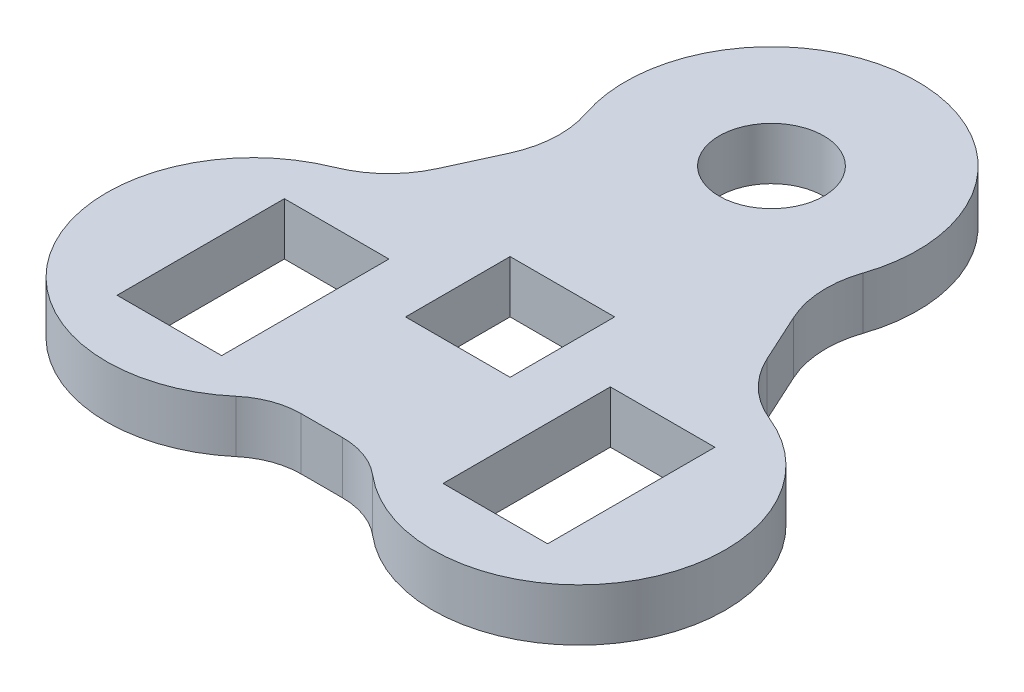
SolidWorks part; units mm, degrees
ref_plane "Front Plane" through (0, 0, 0) normal (0, 0, 1) x (1, 0, 0)
ref_plane "Top Plane" through (0, 0, 0) normal (0, 1, 0) x (1, 0, 0)
ref_plane "Right Plane" through (0, 0, 0) normal (1, 0, 0) x (0, 0, -1)
sketch "Sketch1" plane through (0, 0, 0) normal (0, 1, 0) x (1, 0, 0)
  line L0 (0, 0) -> (0, 300) construction
  line L1 (0, 0) -> (0, -77.4253) construction
  line L2 (0, 0) -> (259.8076, -150) construction
  line L3 (0, 0) -> (-259.8076, -150) construction
  line L4 (0, 60.4932) -> (0, -180) construction
  line L5 (-50, 50) -> (50, 50)
  line L6 (-50, 50) -> (-50, -50)
  line L7 (-50, -50) -> (50, -50)
  line L8 (50, 50) -> (50, -50)
  line L9 (205.8846, -170) -> (105.8846, -170)
  line L10 (-205.8846, -10) -> (-105.8846, -10)
  line L11 (-19.7979, -180) -> (18.2754, -180) construction
  line L12 (-157.6313, 88.0712) -> (-136.6634, 133.755)
  line L13 (-292.3953, -205.546) -> (-11.1841, 407.1433) construction
  line L14 (-117.123, 98.0626) -> (-176.4233, 125.2802) construction
  line L15 (157.6313, 88.0712) -> (136.6634, 133.755)
  line L16 (19.7979, -180) -> (-19.7979, -180)
  line L17 (-205.8846, -10) -> (-205.8846, -170)
  line L18 (-205.8846, -170) -> (-105.8846, -170)
  line L19 (135.9582, 135.2915) -> (136.6634, 133.755)
  line L20 (-135.9582, 135.2915) -> (-136.6634, 133.755)
  line L21 (-105.8846, -10) -> (-105.8846, -170)
  line L22 (-205.8846, -10) -> (-105.8846, -170) construction
  line L23 (-205.8846, -170) -> (-105.8846, -10) construction
  line L24 (105.8846, -10) -> (105.8846, -170)
  line L25 (205.8846, -10) -> (105.8846, -10)
  line L26 (205.8846, -10) -> (205.8846, -170)
  line L27 (-155.8846, -90) -> (-275.7067, -162.3983)
  circle A0 centre (0, 250) radius 50
  arc A1 (132.3634, 205.0564) -> (-132.3634, 205.0564) centre (0, 250) ccw
  arc A2 (-208.1852, 39.8596) -> (-65.2529, -196.6994) centre (-155.8846, -90) ccw
  arc A4 (-19.7979, -180) -> (-65.2529, -196.6994) centre (-19.7979, -250.2128) ccw
  arc A5 (19.7979, -180) -> (65.2529, -196.6994) centre (19.7979, -250.2128) cw
  arc A6 (-157.6313, 88.0712) -> (-208.1852, 39.8596) centre (-243.4699, 127.4693) cw
  arc A7 (-135.9582, 135.2915) -> (-132.3634, 205.0564) centre (-221.7968, 174.6895) ccw
  arc A8 (157.6313, 88.0712) -> (208.1852, 39.8596) centre (243.4699, 127.4693) ccw
  arc A9 (135.9582, 135.2915) -> (132.3634, 205.0564) centre (221.7968, 174.6895) cw
  arc A11 (65.2529, -196.6994) -> (208.1852, 39.8596) centre (155.8846, -90) ccw
  point P23 (0, -180)
  dimension "D3" = 250
  dimension "D5" = 180
  dimension "D1" = 60
  dimension "D2" = 60
  dimension "D4" = 300
  dimension "D6" = 180
  dimension "D7" = 180
  dimension "D8" = 180
  dimension "D9" = 100
  dimension "D10" = 100
extrude "Boss-Extrude1" add sketch "Sketch1" along normal blind 50 contours L20 L12 A6 A2 A4 L16 A5 A11 A8 L15 L19 A9 A1 A7 | L17 L10 L21 L18 | L9 L24 L25 L26 | A0 | L6 L5 L8 L7
sketch3d "3DSketch1"
  line L0 (-206.8457, 250, -38.8398) -> (-65.6839, 250, 196.9361)
  line L1 (-136.2648, 250, 79.0482) -> (-275.6963, 250, 162.5275)
  line L2 (0.3604, 250, 181.6694) -> (0.3604, 250, 1.3094)
  line L3 (207.5666, 250, -38.8398) -> (66.4047, 250, 196.9361)
  line L4 (136.9856, 250, 79.0482) -> (276.4171, 250, 162.5275)
  line L5 (0.3604, 250, -388.8632) -> (0.3604, 250, -249.704)
  line L6 (0.3604, 250, -249.704) -> (132.6177, 250, -203.791)
  line L7 (0.3604, 250, -249.704) -> (-129.9329, 250, -203.791)
  line L8 (-275.6963, 250, 162.5275) -> (-220.5482, 250, 254.6387)
  dimension "D1" = 200
ref_plane "Plane3" through (-274.5297, -0.0735, 164.3642) normal (0.858, 0.0002, -0.5137) x (-0.5137, -0.0001, -0.858)
sketch "Sketch3" plane through (-274.5297, -0.0735, 164.3642) normal (0.858, 0.0002, -0.5137) x (-0.5137, -0.0001, -0.858)
  line L0 (2.2913, 0.0738) -> (2.2913, 50.1852)
  line L1 (2.1408, 250.0738) -> (2.2913, 50.1852)
ref_plane "Plane5" through (-1.177, 0.0011, -1.9659) normal (0.5137, -0.0005, 0.858) x (0.858, 0.0003, -0.5137)
sketch "Sketch5" plane through (-1.177, 0.0011, -1.9659) normal (0.5137, -0.0005, 0.858) x (0.858, 0.0003, -0.5137)
  line L0 (-157.4486, 249.9789) -> (-157.0128, 50.1065)
sketch "Sketch4" plane through (-1.177, 0.0011, -1.9659) normal (0.5137, -0.0005, 0.858) x (0.858, 0.0003, -0.5137)
  line L0 (-319.9599, 250.088) -> (-319.9697, 50.1994) construction
  line L1 (-319.9697, 154.6685) -> (-319.9697, -54.2698) construction
  line L2 (-156.6033, 249.9789) -> (-230.1886, 249.9789) construction
  spline S0 degree 3 poles (-319.9697, 50.1994) (-319.9697, 167.7271) (-245.1663, 254.8296) (-152.1557, 249.7329) (-136.5823, 249.9789) knots 0 0 0 0 0.832545 1 1 1 1
sketch3d "3DSketch3"
  line L0 (-206.8457, 250, -38.8398) -> (-65.6839, 250, 196.9361) construction
  line L1 (-136.0562, 0, 78.5521) -> (-173.7166, 0, 228.8556)
  line L2 (0, 0, 0) -> (-259.8076, 0, 150) construction
  line L3 (-136.0562, 0, 78.5521) -> (-65.2529, 0, 196.6994)
  line L4 (-145.0356, 249.9014, 64.3987) -> (-142.8636, 250.0986, 68.0265) construction
  arc A0 (-208.1852, 0, -39.8596) -> (-65.2529, 0, 196.6994) centre (-155.8846, 0, 90) ccw construction
  arc A1 (-208.1852, 50, -39.8596) -> (-65.2529, 50, 196.6994) centre (-155.8846, 50, 90) ccw construction
  spline S0 degree 3 poles (-65.633, 50, 197.0211) (-66.083, 180.091, 196.2695) (-87.1022, 251.1553, 161.1621) (-142.5921, 250.1232, 68.4799) (-143.9496, 250, 66.2126) knots 0 0 0 0 0.94194 1 1 1 1
  spline S1 degree 3 poles (-206.9921, 50.1279, -39.0842) (-206.48, 180.2181, -38.2288) (-185.4268, 251.2442, -3.0648) (-129.9374, 250.1117, 89.6165) (-128.58, 249.9861, 91.8837) knots 0 0 0 0 0.94194 1 1 1 1
  point P12 (-155.8846, 139.9959, 90)
  point P21 (-155.8846, 189.9959, 90)
  dimension "D1" = 45
ref_plane "Plane6" through (-65.6839, 250, 196.9361) normal (0.5137, 0, 0.858) x (0.858, 0, -0.5137)
sketch "Sketch6" plane through (0, 250, 0) normal (0, 1, 0) x (1, 0, 0)
  line L0 (-222.8211, 0) -> (213.4028, 0) construction
  line L1 (0, 186.4295) -> (0, -206.6386) construction
  line L2 (0, 0) -> (0, 300) construction
  line L3 (-275.7067, -162.3983) -> (0, 0) construction
  line L4 (0, 0) -> (276.4171, -162.5275) construction
  line L5 (0.3604, 388.8632) -> (0, 0) construction
  line L6 (0, 0) -> (132.3634, 205.0564) construction
  line L7 (0, 0) -> (136.6634, 133.755) construction
  line L8 (0, 0) -> (157.6313, 88.0712) construction
  line L9 (-208.1852, 39.8596) -> (0, 0) construction
  line L10 (208.1852, 39.8596) -> (0, 0) construction
  line L11 (0, 0) -> (-157.6313, 88.0712) construction
  line L12 (0, 0) -> (-136.6634, 133.755) construction
  line L13 (0, 0) -> (-132.3634, 205.0564) construction
  line L14 (0, 0) -> (65.2529, -196.6994) construction
  line L15 (-19.7979, -180) -> (0, 0) construction
  line L16 (0, 0) -> (-65.2529, -196.6994) construction
  line L17 (19.7979, -180) -> (0, 0) construction
  line L18 (0, 0) -> (-122.4904, -72.15)
  ellipse E0 centre (0, 0) end of major axis (-150, 0) minor radius 125
ref_plane "Plane8" through (0, 500, 0) normal (0, 1, 0) x (1, 0, 0)
sketch "Sketch10" plane through (0, 500, 0) normal (0, 1, 0) x (1, 0, 0)
  line L0 (0, 0) -> (132.3634, 205.0564)
  line L1 (136.6634, 133.755) -> (0, 0)
  line L2 (157.6313, 88.0712) -> (0, 0)
  line L3 (0, 0) -> (208.1852, 39.8596)
  line L4 (0, 0) -> (65.2529, -196.6994)
  line L5 (19.7979, -180) -> (0, 0)
  line L6 (-275.7067, -162.3983) -> (0, 0)
  line L7 (0, 0) -> (0, -180)
  line L8 (0, 0) -> (0.3604, 388.8632)
  line L9 (275.4052, -162.9091) -> (0, 0)
  line L10 (-20.1316, -179.963) -> (0, 0)
  line L11 (0, 0) -> (-65.6174, -196.5781)
  line L12 (0, 0) -> (-208.111, 40.2454)
  line L13 (-157.4678, 88.3633) -> (0, 0)
  line L14 (-136.4152, 134.0081) -> (0, 0)
  line L15 (0, 0) -> (-131.9831, 205.3014)
  ellipse E0 centre (0, 0) end of major axis (150, 0) minor radius 125
ref_plane "Plane9" through (0, 0, 0) normal (-0.5075, 0, -0.8616) x (-0.8616, 0, 0.5075)
sketch "Sketch11" plane through (0, 0, 0) normal (-0.5075, 0, -0.8616) x (-0.8616, 0, 0.5075)
  line L0 (319.9803, 500) -> (0, 500)
  line L1 (319.9803, 0) -> (319.9803, 50) construction
  line L2 (0, 0) -> (0, 500) construction
  line L3 (0, 250) -> (319.9803, 250) construction
  line L4 (159.9902, 250) -> (159.9902, 500) construction
  line L5 (319.9803, 50) -> (0, 50) construction
  line L6 (159.9902, 250) -> (159.9902, 50) construction
  point P0 (0, 0)
  point P1 (319.9803, 0)
  point P3 (0, 500)
  point P9 (141.8948, 500)
sketch "Sketch12" plane through (0, 0, 0) normal (-0.5075, 0, -0.8616) x (-0.8616, 0, 0.5075)
  line L0 (190.1437, 235.0732) -> (190.1437, 50) construction
  line L1 (319.9803, 50) -> (0, 50) construction
  line L2 (111.3261, 383.0788) -> (190.1437, 383.0788) construction
  line L3 (190.1437, 383.0788) -> (319.9803, 383.0788) construction
  line L4 (141.8948, 500) -> (141.8948, 383.0788) construction
  line L5 (141.8948, 500) -> (111.3261, 500) construction
  line L6 (0, 500) -> (156.3068, 500) construction
  spline S0 degree 3 poles (319.9803, 50) (322.61, 138.9094) (291.9096, 193.8642) (152.8647, 248.5408) (111.0878, 324.4886) (111.0435, 431.2767) (134.8922, 457.3407) (141.8948, 500) knots 0 0 0 0 0.485552 0.56544 0.772941 0.81899 1 1 1 1
ref_plane "Plane13" through (0, 0, 0) normal (0.9486, 0, 0.3166) x (0.3166, 0, -0.9486)
sketch "Sketch15" plane through (0, 0, 0) normal (0.9486, 0, 0.3166) x (0.3166, 0, -0.9486)
  line L0 (-126.9505, 500) -> (-126.9505, -25.9941) construction
  line L1 (0, 250) -> (-126.9505, 250) construction
  line L2 (0, 0) -> (0, 500) construction
  line L3 (0, 500) -> (0, 0) construction
  line L4 (-96.0656, 50) -> (-96.0656, 235.07) construction
  spline S0 degree 3 poles (-207.24, 50) (-215.0405, 148.3825) (-182.9916, 187.9638) (-118.6428, 263.7128) (-104.275, 342.9232) (-109.4834, 423.1888) (-126.2807, 450.1551) (-126.9505, 500) knots 0 0 0 0 0.374207 0.446384 0.691163 0.749585 1 1 1 1
  point P0 (-207.24, 50)
  point P1 (-207.24, 0)
  point P3 (0, 0)
  point P5 (0, 500)
  point P7 (-126.9505, 500)
sketch "Sketch16" plane through (0, 50, 0) normal (0, 1, 0) x (1, 0, 0)
  arc A0 (-65.2529, -196.6994) -> (-275.7067, -162.3983) centre (-155.8846, -90) cw
sketch "Sketch17" plane through (0, 500, 0) normal (0, 1, 0) x (1, 0, 0)
  spline S0 degree 3 poles (-122.2618, -72.0153) (-103.1621, -95.2023) (-73.8474, -112.0827) (-40.1956, -120.419) knots 0 0 0 0 1 1 1 1
other "Boundary-Surface2"
sketch "Sketch18" plane through (0, 50, 0) normal (0, 1, 0) x (1, 0, 0)
  line L1 (132.3634, 205.0564) -> (-132.3634, 205.0564)
  line L2 (65.2529, -196.6994) -> (208.1852, 39.8596)
  line L3 (0, 0) -> (0, -180) construction
  line L4 (-208.1852, 39.8596) -> (-65.2529, -196.6994)
  arc A0 (-132.3634, 205.0564) -> (132.3634, 205.0564) centre (0, 250) cw
  arc A1 (65.2529, -196.6994) -> (208.1852, 39.8596) centre (155.8846, -90) ccw
  arc A2 (-208.1852, 39.8596) -> (-65.2529, -196.6994) centre (-155.8846, -90) ccw
sketch "Sketch19" plane through (0, 50, 0) normal (0, 1, 0) x (1, 0, 0)
